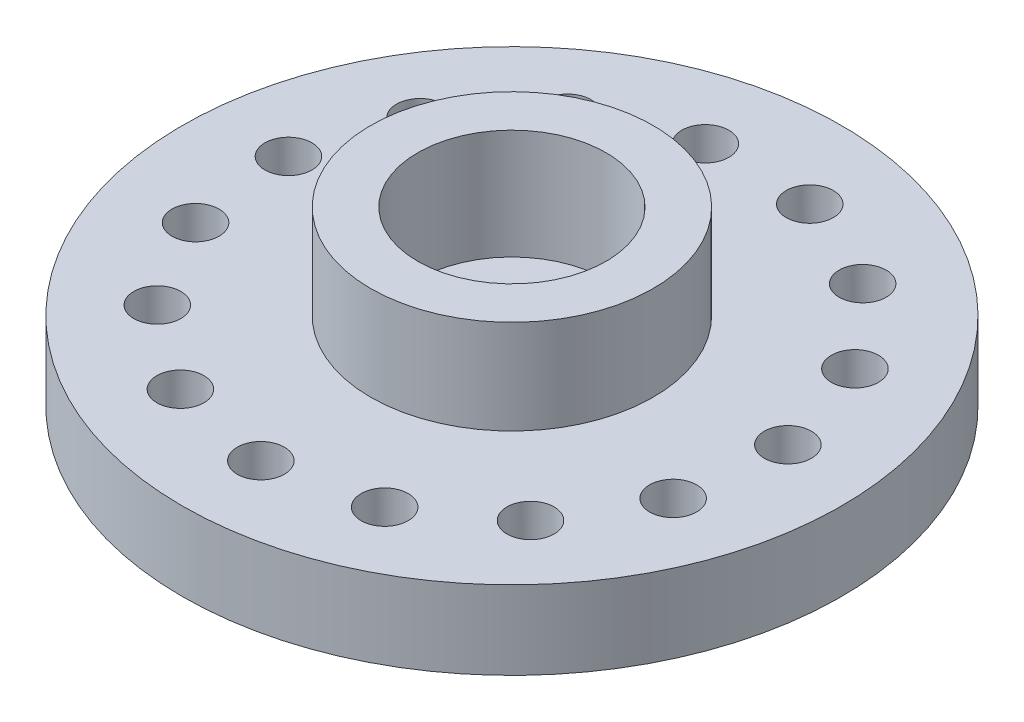
SolidWorks part; units mm, degrees
ref_plane "前视基准面" through (0, 0, 0) normal (0, 0, 1) x (1, 0, 0)
ref_plane "上视基准面" through (0, 0, 0) normal (0, 1, 0) x (1, 0, 0)
ref_plane "右视基准面" through (0, 0, 0) normal (1, 0, 0) x (0, 0, -1)
sketch "草图1" plane through (0, 0, 0) normal (0, 1, 0) x (1, 0, 0)
  circle A0 centre (0, 0) radius 10.5
  dimension "D1" = 21
extrude "凸台-拉伸1" add sketch "草图1" along normal blind 2.5
sketch "草图2" plane through (0, 2.5, 0) normal (0, 1, 0) x (1, 0, 0)
  circle A0 centre (0, 0) radius 4.5
  dimension "D1" = 9
extrude "凸台-拉伸2" add sketch "草图2" along normal blind 3
sketch "草图3" plane through (0, 5.5, 0) normal (0, 1, 0) x (1, 0, 0)
  circle A0 centre (0, 0) radius 3
  dimension "D1" = 6
extrude "切除-拉伸1" cut sketch "草图3" against normal blind 3.5
sketch "草图4" plane through (0, 0, 0) normal (0, -1, 0) x (1, 0, 0)
  circle A0 centre (0, 0) radius 8 construction
  circle A1 centre (0, 8) radius 0.75
  circle A2 centre (3.2539, 7.3084) radius 0.75
  circle A3 centre (5.9452, 5.353) radius 0.75
  circle A4 centre (7.6085, 2.4721) radius 0.75
  circle A5 centre (7.9562, -0.8362) radius 0.75
  circle A6 centre (6.9282, -4) radius 0.75
  circle A7 centre (4.7023, -6.4721) radius 0.75
  circle A8 centre (1.6633, -7.8252) radius 0.75
  circle A9 centre (-1.6633, -7.8252) radius 0.75
  circle A10 centre (-4.7023, -6.4721) radius 0.75
  circle A11 centre (-6.9282, -4) radius 0.75
  circle A12 centre (-7.9562, -0.8362) radius 0.75
  circle A13 centre (-7.6085, 2.4721) radius 0.75
  circle A14 centre (-5.9452, 5.353) radius 0.75
  circle A15 centre (-3.2539, 7.3084) radius 0.75
  point P36 (0, 0)
  dimension "D1" = 16
  dimension "D2" = 1.5
  dimension "D3" = 15
extrude "切除-拉伸2" cut sketch "草图4" against normal blind 4
